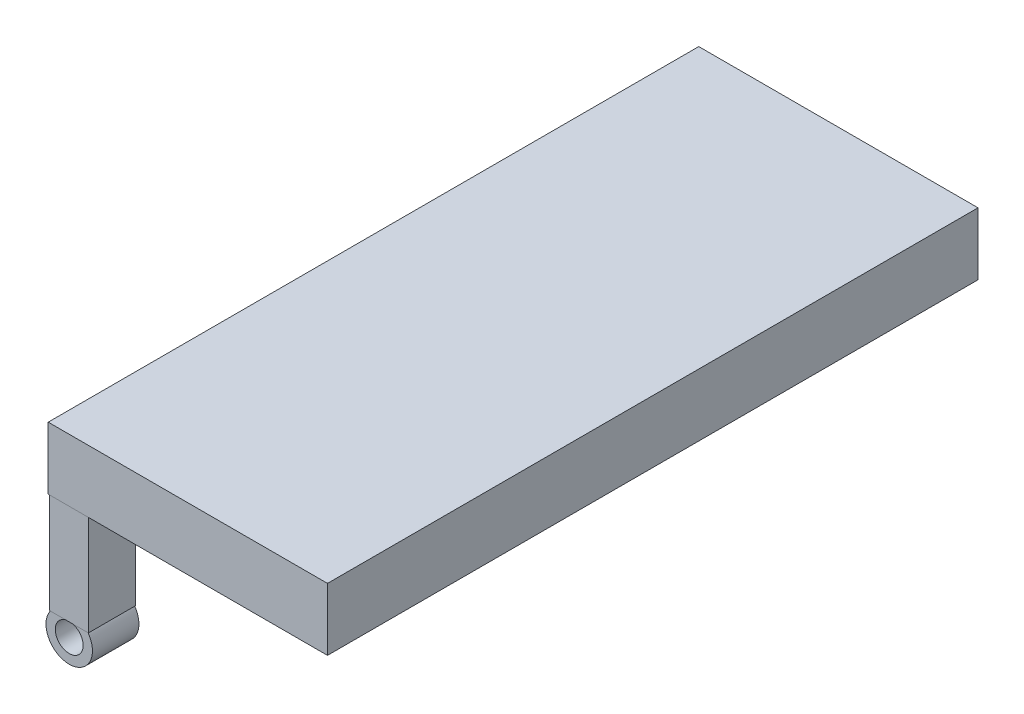
SolidWorks part; units mm, degrees
ref_plane "前视基准面" through (0, 0, 0) normal (0, 0, 1) x (1, 0, 0)
ref_plane "上视基准面" through (0, 0, 0) normal (0, 1, 0) x (1, 0, 0)
ref_plane "右视基准面" through (0, 0, 0) normal (1, 0, 0) x (0, 0, -1)
other "Configuration Table"
sketch "草图1" plane through (0, 0, 0) normal (0, 0, 1) x (1, 0, 0)
  circle A0 centre (0, 0) radius 5
  dimension "D1" = 10
extrude "凸台-拉伸1" add sketch "草图1" along normal blind 10 contours A0
sketch "草图2" plane through (0, 0, 10) normal (0, 0, 1) x (1, 0, 0)
  circle A0 centre (0, 0) radius 3
  dimension "D1" = 6
extrude "切除-拉伸1" cut sketch "草图2" against normal blind 8
sketch "草图4" plane through (0, 0, 10) normal (0, 0, 1) x (1, 0, 0)
  line L1 (-4.1766, 5.9563) -> (4.2174, 5.9563)
  line L2 (-4.1766, 5.9563) -> (-4.1766, 2.9948)
  line L3 (-4.1766, 2.9948) -> (4.2174, 2.9948)
  line L4 (4.2174, 5.9563) -> (4.2174, 2.9948)
  point P4 (4.2174, 5.9563)
extrude "凸台-拉伸2" add sketch "草图4" along normal blind 0.1 and the other way blind 10
sketch "草图5" plane through (0, 5.9563, 0) normal (0, 1, 0) x (1, 0, 0)
  line L0 (4.2174, -10.1) -> (-4.1766, -10.1) construction
  line L1 (-4.1766, -10.1) -> (4.2174, -10.1)
  line L2 (-4.1766, -10.1) -> (-4.1766, 0)
  line L3 (-4.1766, 0) -> (4.2174, 0)
  line L4 (4.2174, -10.1) -> (4.2174, 0)
  line L5 (-4.1766, 0) -> (-4.1766, -10.1) construction
  line L6 (4.2174, 0) -> (4.2174, -10.1) construction
  point P8 (4.2174, 0)
extrude "凸台-拉伸3" add sketch "草图5" along normal blind 30
sketch "草图6" plane through (-4.1766, 0, 0) normal (-1, 0, 0) x (0, 0, 1)
  line L1 (-129.7549, 38.1124) -> (10.2451, 38.1124)
  line L2 (-129.7549, 38.1124) -> (-129.7549, 24.6901)
  line L3 (-129.7549, 24.6901) -> (10.2451, 24.6901)
  line L4 (10.2451, 38.1124) -> (10.2451, 24.6901)
  dimension "D1" = 140
extrude "凸台-拉伸4" add sketch "草图6" along normal blind 0.1 and the other way blind 60
